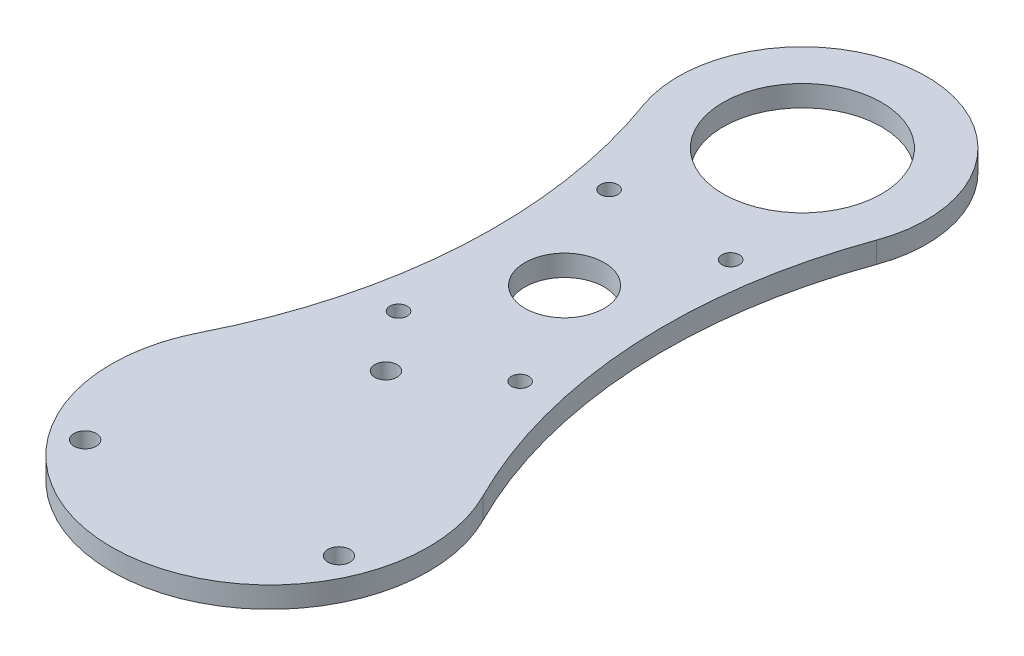
SolidWorks part; units mm, degrees
material "1060 合金"
ref_plane "前视基准面" through (0, 0, 0) normal (0, 0, 1) x (1, 0, 0)
ref_plane "上视基准面" through (0, 0, 0) normal (0, 1, 0) x (1, 0, 0)
ref_plane "右视基准面" through (0, 0, 0) normal (1, 0, 0) x (0, 0, -1)
sketch "草图1" plane through (0, 0, 0) normal (0, 1, 0) x (1, 0, 0)
  line L0 (0, 0) -> (0, 100.74)
  circle A0 centre (0, 0) radius 30
  circle A1 centre (0, 100.74) radius 23.5
  arc A2 (-26.7852, 13.5111) -> (-22.0861, 92.7116) centre (-116.0694, 58.5482) ccw
  arc A3 (22.0861, 92.7116) -> (26.7852, 13.5111) centre (116.0694, 58.5482) ccw
  dimension "D2" = 60
  dimension "D3" = 47
  dimension "D4" = 200
  dimension "D5" = 200
  dimension "D1" = 100.74
extrude "凸台-拉伸1" add sketch "草图1" along normal blind 4
sketch "草图2" plane through (0, 4, 0) normal (0, 1, 0) x (1, 0, 0)
  line L0 (0, 0) -> (25, 0)
  line L1 (25, 0) -> (0, 0)
  line L2 (0, 0) -> (22.9525, -9.9087)
  circle A0 centre (0, 0) radius 25
  circle A1 centre (22.9525, -9.9087) radius 2.1
  dimension "D1" = 50
  dimension "D3" = 4.2
  dimension "D2" = 23.35
extrude "切除-拉伸1" cut sketch "草图2" against normal blind 4 contours A0 A1 | L2 A1 A0 | A0 A1 L2
pattern_circular "阵列(圆周)1" count 3 over 360 about axis through (0, 0, 0) along (0, 1, 0) of "切除-拉伸1"
sketch "草图4" plane through (0, 0, 0) normal (0, -1, 0) x (-1, 0, 0)
  circle A0 centre (0, 55.74) radius 7.5
  arc A1 (22.0861, 92.7116) -> (-22.0861, 92.7116) centre (0, 100.74) ccw construction
  dimension "D1" = 45
  dimension "D2" = 15
extrude "切除-拉伸2" cut sketch "草图4" against normal blind 27.5
sketch "草图5" plane through (0, 0, 0) normal (0, -1, 0) x (1, 0, 0)
  line L1 (-11.5, -35.8214) -> (11.5, -35.8214)
  line L2 (-11.5, -35.8214) -> (-11.5, -75.6586)
  line L3 (-11.5, -75.6586) -> (11.5, -75.6586)
  line L4 (11.5, -35.8214) -> (11.5, -75.6586)
  line L5 (-11.5, -35.8214) -> (11.5, -75.6586) construction
  line L6 (-11.5, -75.6586) -> (11.5, -35.8214) construction
  circle A0 centre (0, -55.74) radius 23
  circle A1 centre (-11.5, -35.8214) radius 1.65
  circle A2 centre (11.5, -35.8214) radius 1.65
  dimension "D1" = 46
  dimension "D3" = 3.3
  dimension "D4" = 3.3
  dimension "D2" = 60
extrude "切除-拉伸3" cut sketch "草图5" against normal blind 27.5 contours L2 A1 L1 | L1 A1 A0 | A0 A1 L2 | A0 A1 | A0 A2 | L1 A2 L4 | A0 A2 L1 | L4 A2 A0
pattern_circular "阵列(圆周)2" count 3 over 360 about axis through (0, 0, -55.74) along (0, 1, 0) of "切除-拉伸3"
sketch "草图6" plane through (0, 0, 0) normal (0, -1, 0) x (1, 0, 0)
  circle A0 centre (0, -100.74) radius 15
  dimension "D1" = 30
extrude "切除-拉伸4" cut sketch "草图6" against normal blind 29.5
